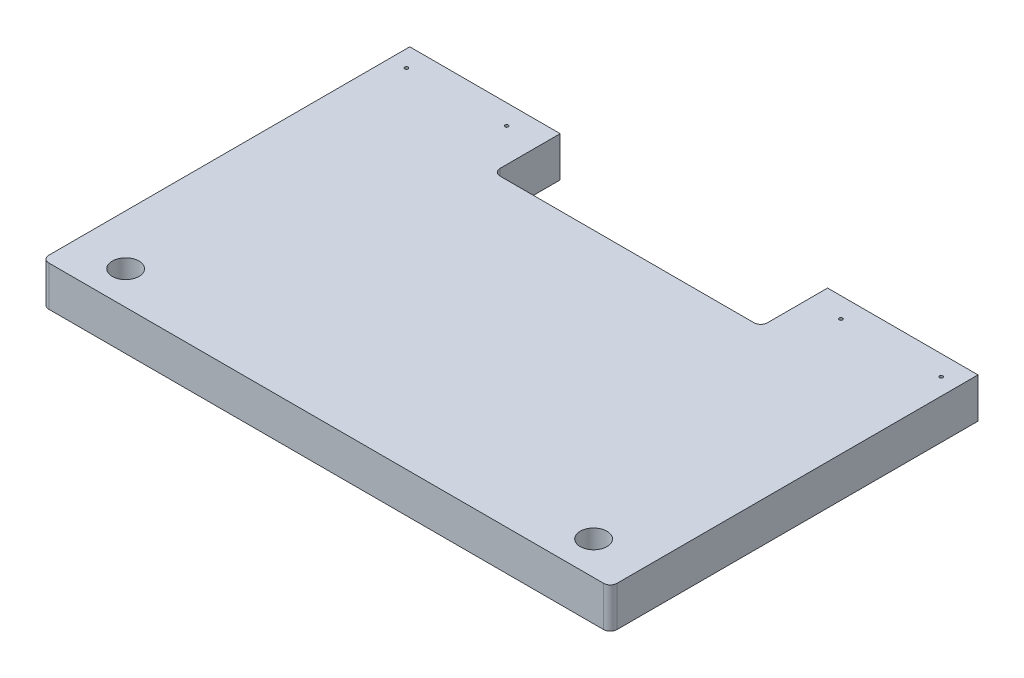
SolidWorks part; units mm, degrees
ref_plane "Front Plane" through (0, 0, 0) normal (0, 0, 1) x (1, 0, 0)
ref_plane "Top Plane" through (0, 0, 0) normal (0, 1, 0) x (1, 0, 0)
ref_plane "Right Plane" through (0, 0, 0) normal (1, 0, 0) x (0, 0, -1)
sketch "Sketch1" plane through (0, 0, 0) normal (0, 1, 0) x (1, 0, 0)
  line L0 (85, 110) -> (85, 0) construction
  line L1 (0, 0) -> (170, 0)
  line L2 (0, 0) -> (0, 110)
  line L3 (0, 110) -> (45, 110)
  line L4 (170, 0) -> (170, 110)
  line L5 (0, 104) -> (170, 104) construction
  line L6 (45, 110) -> (45, 90)
  line L7 (45, 90) -> (125, 90)
  line L8 (125, 90) -> (125, 110)
  line L9 (125, 110) -> (170, 110)
  circle A0 centre (155, 10) radius 4
  circle A1 centre (15, 10) radius 4
  circle A2 centre (5, 104) radius 0.5
  circle A3 centre (35, 104) radius 0.5
  circle A4 centre (165, 104) radius 0.5
  circle A5 centre (135, 104) radius 0.5
  point P25 (85, 90)
  dimension "D3" = 8
  dimension "D7" = 1
  dimension "D1" = 170
  dimension "D2" = 110
  dimension "D4" = 15
  dimension "D5" = 10
  dimension "D6" = 6
  dimension "D8" = 5
  dimension "D9" = 30
  dimension "D10" = 45
  dimension "D11" = 20
extrude "Boss-Extrude1" add sketch "Sketch1" along normal blind 12
fillet "Fillet1" radius 2 4 edges at (170, 6, 0) (0, 6, 0) (125, 6, -90) (45, 6, -90)
